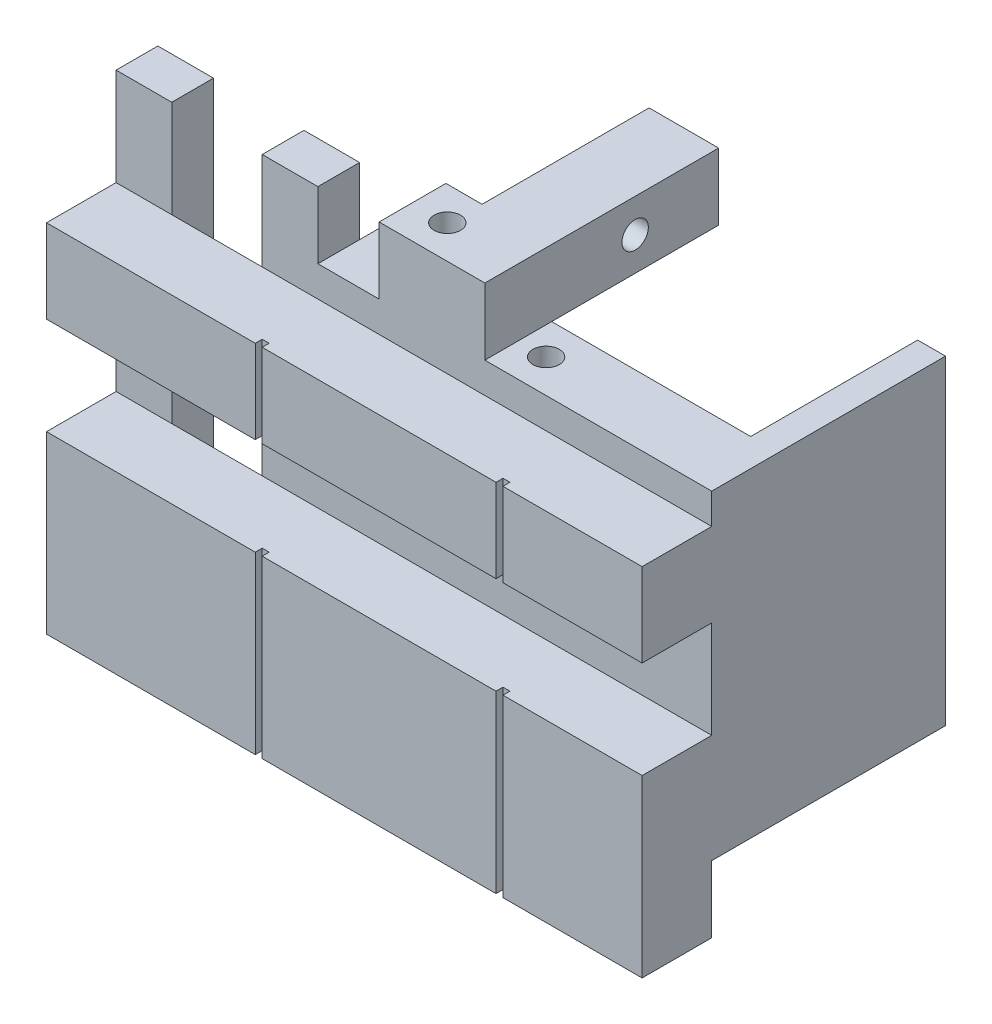
SolidWorks part; units mm, degrees
ref_plane "前视基准面" through (0, 0, 0) normal (0, 0, 1) x (1, 0, 0)
ref_plane "上视基准面" through (0, 0, 0) normal (0, 1, 0) x (1, 0, 0)
ref_plane "右视基准面" through (0, 0, 0) normal (1, 0, 0) x (0, 0, -1)
other "Configuration Table"
sketch "草图1" plane through (0, 0, 0) normal (0, 0, 1) x (1, 0, 0)
  line L0 (12, 0) -> (28.3, 0)
  line L1 (0, 0) -> (4.4, 0)
  line L2 (0, 0) -> (0, -23)
  line L3 (0, -23) -> (4.4, -23)
  line L4 (28.3, 0) -> (28.3, -23)
  line L6 (12, 0) -> (12, 4.8)
  line L7 (12, 4.8) -> (4.4, 4.8)
  line L8 (4.4, 0) -> (4.4, 4.8)
  line L10 (12, -23) -> (12, -27.8)
  line L11 (12, -27.8) -> (4.4, -27.8)
  line L12 (4.4, -23) -> (4.4, -27.8)
  line L13 (12, -23) -> (28.3, -23)
  dimension "D1" = 28.3
  dimension "D2" = 23
  dimension "D3" = 16.3
  dimension "D4" = 16.3
  dimension "D5" = 7.6
  dimension "D6" = 7.6
  dimension "D7" = 4.8
  dimension "D8" = 4.8
extrude "凸台-拉伸1" add sketch "草图1" against normal blind 4.8
sketch "草图2" plane through (0, 0, -4.8) normal (0, 0, -1) x (-1, 0, 0)
  line L0 (-12, -23) -> (-28.3, -23) construction
  line L1 (-28.3, 0) -> (-26.3, 0)
  line L2 (-28.3, 0) -> (-28.3, -23)
  line L3 (-28.3, -23) -> (-26.3, -23)
  line L4 (-26.3, 0) -> (-26.3, -23)
  line L6 (-12, -27.8) -> (-7, -27.8)
  line L7 (-12, -27.8) -> (-12, -23)
  line L8 (-12, -23) -> (-7, -23)
  line L9 (-7, -27.8) -> (-7, -23)
  line L10 (-12, 4.8) -> (-7, 4.8)
  line L11 (-12, 4.8) -> (-12, 0)
  line L12 (-12, 0) -> (-7, 0)
  line L13 (-7, 4.8) -> (-7, 0)
  dimension "D1" = 5
  dimension "D2" = 5
  dimension "D3" = 2
extrude "凸台-拉伸2" add sketch "草图2" along normal blind 12
sketch "草图3" plane through (7, 0, 0) normal (-1, 0, 0) x (0, 0, 1)
  line L0 (-16.8, 2.4) -> (49983.2, 2.4) construction
  line L1 (-16.8, 0) -> (-16.8, 4.8) construction
  line L2 (-10.8, 4.8) -> (-10.8, -49995.2) construction
  line L3 (-16.8, 4.8) -> (-4.8, 4.8) construction
  line L4 (-16.8, -25.4) -> (49983.2, -25.4) construction
  line L5 (-16.8, -27.8) -> (-16.8, -23) construction
  circle A0 centre (-10.8, 2.4) radius 0.95
  circle A1 centre (-10.8, -25.4) radius 0.95
  point P4 (-16.8, 2.4)
  point P9 (-10.8, 4.8)
  point P14 (-16.8, -25.4)
  dimension "D1" = 1.9
  dimension "D2" = 1.9
extrude "切除-拉伸1" cut sketch "草图3" against normal blind 5
sketch "草图6" plane through (0, 0, 0) normal (0, 1, 0) x (1, 0, 0)
  line L0 (12, 16.8) -> (12, 0) construction
  line L1 (26.3, 4.8) -> (12, 4.8) construction
  circle A0 centre (14, 2.4) radius 0.95
  dimension "D3" = 1.9
  dimension "D1" = 2
  dimension "D2" = 2.4
extrude "切除-拉伸4" cut sketch "草图6" against normal blind 32
sketch "草图8" plane through (0, 0, 0) normal (0, 0, 1) x (1, 0, 0)
  line L0 (28.3, 0) -> (12, 0) construction
  line L1 (0, 0) -> (0, -23) construction
  line L2 (-14.5, -2.2) -> (28.3, -2.2)
  line L3 (-14.5, -2.2) -> (-14.5, -8.2)
  line L4 (-14.5, -8.2) -> (28.3, -8.2)
  line L5 (28.3, -2.2) -> (28.3, -8.2)
  line L6 (28.3, -23) -> (28.3, 0) construction
  line L11 (-14.2474, -15.2) -> (49985.7526, -15.2) construction
  line L12 (4.4, -27.8) -> (12, -27.8) construction
  line L13 (28.3, -15.2) -> (-14.5, -15.2)
  line L14 (28.3, -15.2) -> (28.3, -27.8)
  line L15 (28.3, -27.8) -> (-14.5, -27.8)
  line L16 (-14.5, -15.2) -> (-14.5, -27.8)
  dimension "D1" = 6
  dimension "D2" = 2.2
  dimension "D3" = 7
  dimension "D5" = 14.5
extrude "凸台-拉伸3" add sketch "草图8" along normal blind 5
sketch "草图9" plane through (0, 0, 0) normal (0, 0, -1) x (-1, 0, 0)
  line L0 (0, 0) -> (0, -23) construction
  line L1 (0, 4.8) -> (4, 4.8)
  line L2 (0, 4.8) -> (0, -27.8)
  line L3 (0, -27.8) -> (4, -27.8)
  line L4 (4, 4.8) -> (4, -27.8)
  line L5 (10.5, 4.8) -> (14.5, 4.8)
  line L6 (10.5, 4.8) -> (10.5, -27.8)
  line L7 (10.5, -27.8) -> (14.5, -27.8)
  line L8 (14.5, 4.8) -> (14.5, -27.8)
  line L9 (14.5, -27.8) -> (-4.4, -27.8) construction
  line L10 (-7, 4.8) -> (-4.4, 4.8) construction
  dimension "D1" = 4
  dimension "D2" = 4
extrude "凸台-拉伸4" add sketch "草图9" along normal blind 3
sketch "草图11" plane through (0, -23, 0) normal (0, -1, 0) x (-1, 0, 0)
  line L0 (-14, 2.4) -> (49986, 2.4) construction
  line L1 (-7, -6.5072) -> (-7, 49993.4928) construction
  line L2 (-14, 2.4) -> (-14, 50002.4) construction
  circle A0 centre (-6.9, 2.4) radius 0.95
  dimension "D2" = 1.9
  dimension "D1" = 7
extrude "切除-拉伸5" cut sketch "草图11" against normal through all and the other way through all
sketch "草图12" plane through (0, 0, 5) normal (0, 0, 1) x (1, 0, 0)
  line L0 (28.3, -2.2) -> (-4, -2.2) construction
  line L1 (0.5, -2.2) -> (1, -2.2)
  line L2 (0.5, -2.2) -> (0.5, -27.8)
  line L3 (0.5, -27.8) -> (1, -27.8)
  line L4 (1, -2.2) -> (1, -27.8)
  line L5 (-14.5, -27.8) -> (28.3, -27.8) construction
  line L6 (-14.5, -15.2) -> (-14.5, -27.8) construction
  line L7 (17.8, -2.2) -> (18.3, -2.2)
  line L8 (17.8, -2.2) -> (17.8, -27.8)
  line L9 (17.8, -27.8) -> (18.3, -27.8)
  line L10 (18.3, -2.2) -> (18.3, -27.8)
  line L11 (28.3, -27.8) -> (28.3, -15.2) construction
  dimension "D1" = 0.5
  dimension "D2" = 0.5
  dimension "D3" = 15
  dimension "D4" = 10
extrude "切除-拉伸6" cut sketch "草图12" against normal blind 0.5
